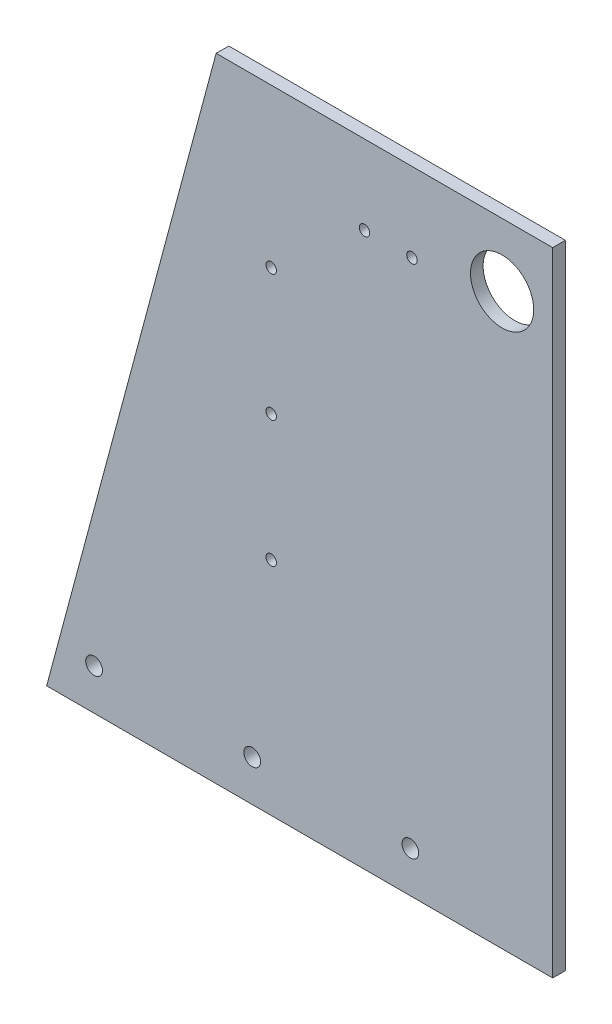
SolidWorks part; units mm, degrees
ref_plane "前视基准面" through (0, 0, 0) normal (0, 0, 1) x (1, 0, 0)
ref_plane "上视基准面" through (0, 0, 0) normal (0, 1, 0) x (1, 0, 0)
ref_plane "右视基准面" through (0, 0, 0) normal (1, 0, 0) x (0, 0, -1)
other "Configuration Table"
sketch "草图2" plane through (0, 0, 0) normal (0, 0, 1) x (1, 0, 0)
  line L0 (-26.4102, 100) -> (-80, -100)
  line L1 (-80, 100) -> (80, 100)
  line L2 (-80, 100) -> (-80, -100)
  line L3 (-80, -100) -> (80, -100)
  line L4 (80, 100) -> (80, -100)
  line L5 (-80, 100) -> (80, -100) construction
  line L6 (-80, -100) -> (80, 100) construction
  line L7 (28, 100) -> (28, -100) construction
  circle A0 centre (-9, 50) radius 1.65
  circle A1 centre (-9, 10) radius 1.65
  circle A2 centre (-9, -30) radius 1.65
  circle A3 centre (20.5, 75) radius 1.65
  circle A4 centre (35.5, 75) radius 1.65
  circle A5 centre (64, 80) radius 10
  circle A6 centre (-65, -87) radius 2.65
  circle A7 centre (-15, -87) radius 2.65
  circle A8 centre (35, -87) radius 2.65
  circle A9 centre (85, -87) radius 2.65
  point P0 (0, 0)
  dimension "D5" = 3.3
  dimension "D9" = 3.3
  dimension "D12" = 20
  dimension "D15" = 5.3
  dimension "D2" = 160
  dimension "D3" = 200
  dimension "D4" = 40
  dimension "D6" = 89
  dimension "D7" = 50
  dimension "D8" = 52
  dimension "D10" = 15
  dimension "D11" = 25
  dimension "D13" = 20
  dimension "D14" = 13
  dimension "D16" = 15
  dimension "D18" = 75
  dimension "D1" = 3
  dimension "D17" = 4
extrude "凸台-拉伸1" add sketch "草图2" along normal blind 4 contours L4 L1 L0 L3 A2 A1 A0
